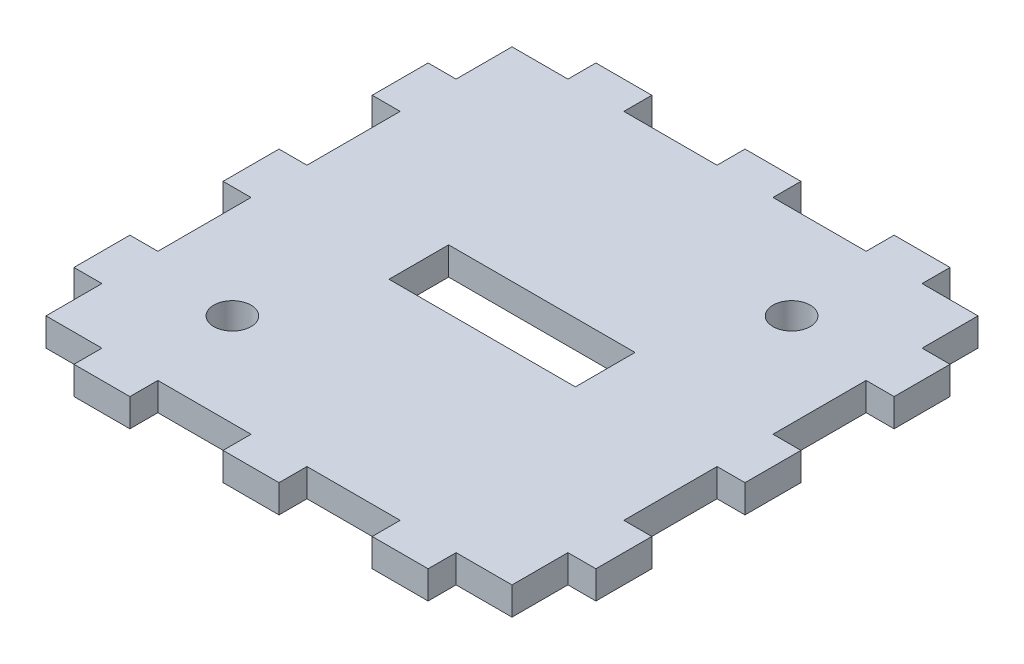
SolidWorks part; units mm, degrees
material "Acrylic (Medium-high impact)"
ref_plane "Front Plane" through (0, 0, 0) normal (0, 0, 1) x (1, 0, 0)
ref_plane "Top Plane" through (0, 0, 0) normal (0, 1, 0) x (1, 0, 0)
ref_plane "Right Plane" through (0, 0, 0) normal (1, 0, 0) x (0, 0, -1)
sketch "Sketch1" plane through (0, 0, 0) normal (0, 1, 0) x (1, 0, 0)
  line L0 (-53, 44) -> (-50, 44)
  line L1 (0, 0) -> (-50, 0)
  line L2 (0, 0) -> (0, 50)
  line L3 (0, 50) -> (-50, 50)
  line L4 (-50, 0) -> (-50, 50)
  line L6 (-50, 50) -> (-50, 0)
  line L8 (-53, 44) -> (-53, 38)
  line L9 (-50, 50) -> (0, 50)
  line L11 (-44, 53) -> (-38, 53)
  line L21 (-53, 28) -> (-50, 28)
  line L22 (-53, 22) -> (-50, 22)
  line L23 (-53, 6) -> (-50, 6)
  line L24 (-25, 50) -> (-25, 0) construction
  line L25 (-50, 25) -> (0, 25) construction
  line L26 (-44, 53) -> (-44, 50)
  line L27 (-28, 53) -> (-28, 50)
  line L28 (-12, 53) -> (-12, 50)
  line L29 (-6, 53) -> (-6, 50)
  line L30 (-38, 53) -> (-38, 50)
  line L31 (-22, 53) -> (-22, 50)
  line L32 (-44, 53) -> (-38, 53)
  line L33 (-28, 53) -> (-22, 53)
  line L34 (-12, 53) -> (-6, 53)
  line L35 (-53, 38) -> (-50, 38)
  line L36 (-53, 38) -> (-53, 44)
  line L37 (-53, 28) -> (-53, 22)
  line L38 (-53, 12) -> (-50, 12)
  line L39 (-53, 12) -> (-53, 6)
  line L40 (-28, 53) -> (-22, 53)
  line L41 (-12, 53) -> (-6, 53)
  line L42 (-53, 28) -> (-53, 22)
  line L43 (-53, 12) -> (-53, 6)
  line L44 (-38, 51.5) -> (-28, 51.5) construction
  line L45 (-22, 51.5) -> (-12, 51.5) construction
  line L46 (-51.5, 28) -> (-51.5, 38) construction
  line L47 (-51.5, 12) -> (-51.5, 22) construction
  line L48 (3, 6) -> (0, 6)
  line L49 (3, 12) -> (3, 6)
  line L50 (3, 12) -> (0, 12)
  line L51 (3, 22) -> (0, 22)
  line L52 (3, 28) -> (3, 22)
  line L53 (3, 28) -> (0, 28)
  line L54 (3, 38) -> (0, 38)
  line L55 (3, 44) -> (3, 38)
  line L56 (3, 44) -> (0, 44)
  line L57 (-12, -3) -> (-12, 0)
  line L58 (-22, -3) -> (-22, 0)
  line L59 (-28, -3) -> (-28, 0)
  line L60 (-38, -3) -> (-38, 0)
  line L61 (-6, -3) -> (-6, 0)
  line L62 (-12, -3) -> (-6, -3)
  line L63 (-28, -3) -> (-22, -3)
  line L64 (-44, -3) -> (-38, -3)
  line L65 (-44, -3) -> (-44, 0)
  dimension "D1" = 50
  dimension "D2" = 50
  dimension "D3" = 3
  dimension "D4" = 6
  dimension "D5" = 6
  dimension "D6" = 6
  dimension "D7" = 6
  dimension "D8" = 6
extrude "Boss-Extrude1" add sketch "Sketch1" along normal blind 3 contours L38 L39 L23 L6 | L21 L37 L22 L6 | L8 L35 L4 L0 | L30 L11 L26 L3 | L4 L1 L2 L3 L9 L6 | L33 L27 L3 L31 | L34 L28 L9 L29 | L55 L56 L2 L54 | L52 L53 L2 L51 | L49 L50 L2 L48 | L57 L62 L61 L1 | L59 L63 L58 L1 | L65 L64 L60 L1
sketch "Sketch2" plane through (0, 3, 0) normal (0, 1, 0) x (1, 0, 0)
  line L0 (3, 28) -> (3, 22) construction
  line L1 (-35, 28.2) -> (-15, 28.2)
  line L2 (-35, 28.2) -> (-35, 21.8)
  line L3 (-35, 21.8) -> (-15, 21.8)
  line L4 (-15, 28.2) -> (-15, 21.8)
  line L5 (-28, -3) -> (-22, -3) construction
  line L6 (-28, 0) -> (-38, 0) construction
  line L7 (-50, 12) -> (-50, 22) construction
  line L8 (0, 44) -> (0, 50) construction
  line L9 (0, 50) -> (-6, 50) construction
  circle A0 centre (-40, 10) radius 2
  circle A1 centre (-10, 40) radius 2
  point P4 (-15, 25)
  point P7 (3, 25)
  point P8 (-25, 21.8)
  point P11 (-25, -3)
  dimension "D3" = 4
  dimension "D1" = 6.4
  dimension "D2" = 20
  dimension "D4" = 10
  dimension "D5" = 10
  dimension "D6" = 10
  dimension "D7" = 10
extrude "Cut-Extrude1" cut sketch "Sketch2" against normal through all
